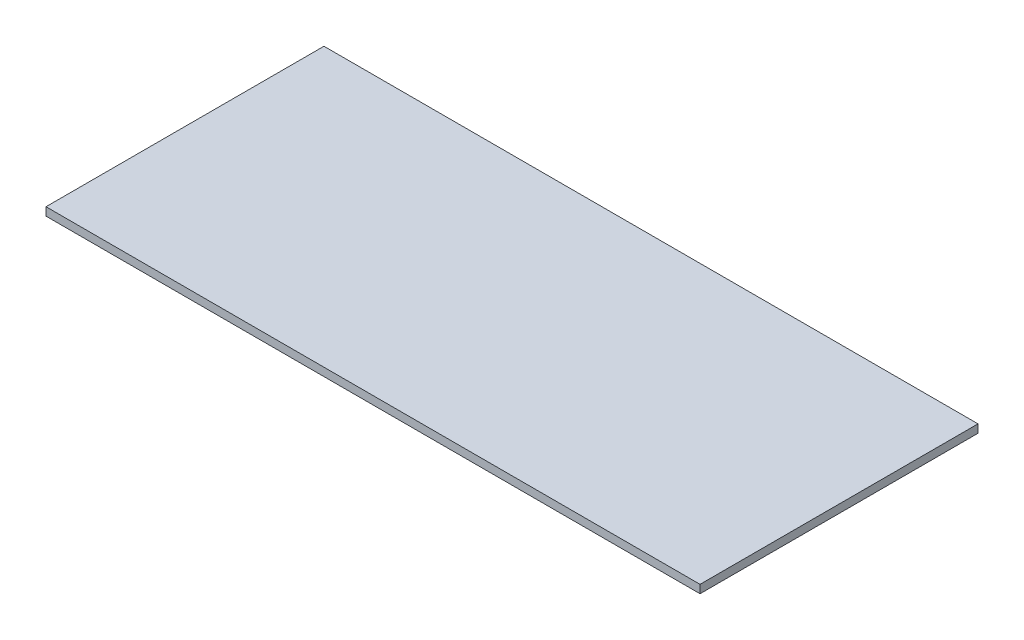
SolidWorks part; units mm, degrees
ref_plane "Front Plane" through (0, 0, 0) normal (0, 0, 1) x (1, 0, 0)
ref_plane "Top Plane" through (0, 0, 0) normal (0, 1, 0) x (1, 0, 0)
ref_plane "Right Plane" through (0, 0, 0) normal (1, 0, 0) x (0, 0, -1)
sketch "Sketch2" plane through (0, 0, 0) normal (0, 1, 0) x (1, 0, 0)
  line L6 (-254, -107.95) -> (254, -107.95)
  line L7 (-254, -107.95) -> (-254, 107.95)
  line L8 (-254, 107.95) -> (254, 107.95)
  line L17 (254, -107.95) -> (254, 107.95)
  line L18 (-254, -107.95) -> (254, 107.95) construction
  line L19 (-254, 107.95) -> (254, -107.95) construction
  point P0 (0, 0)
  dimension "D1" = 215.9
  dimension "D2" = 508
extrude "Boss-Extrude2" add sketch "Sketch2" along normal blind 6.35
